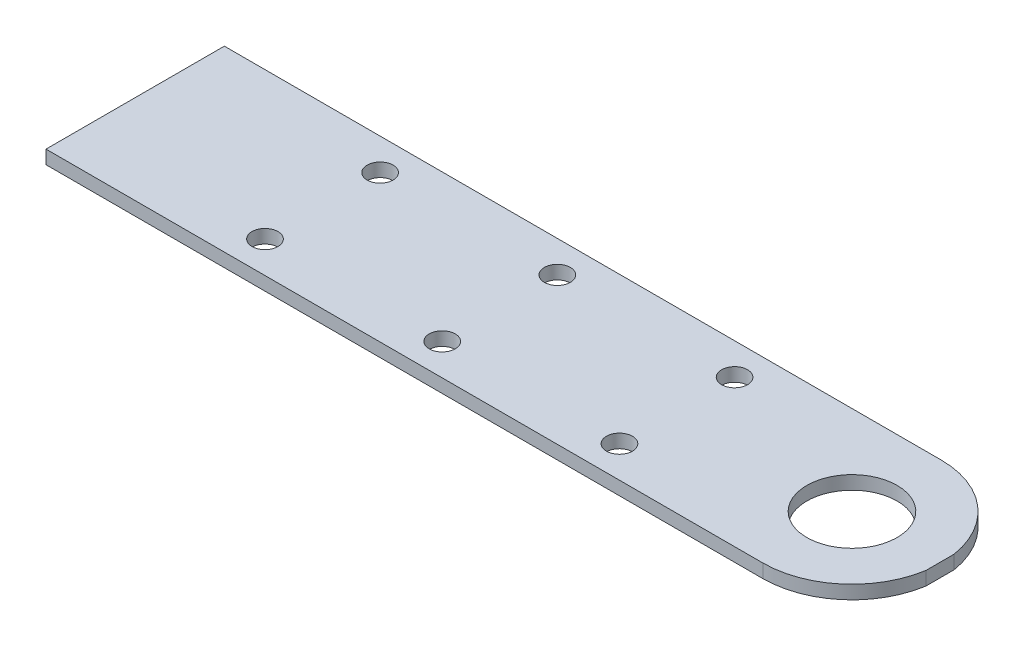
SolidWorks part; units mm, degrees
ref_plane "Front Plane" through (0, 0, 0) normal (0, 0, 1) x (1, 0, 0)
ref_plane "Top Plane" through (0, 0, 0) normal (0, 1, 0) x (1, 0, 0)
ref_plane "Right Plane" through (0, 0, 0) normal (1, 0, 0) x (0, 0, -1)
sketch "Sketch1" plane through (0, 0, 0) normal (0, 1, 0) x (1, 0, 0)
  line L0 (-69.469, 16.51) -> (-49.53, 16.51) construction
  line L1 (0, 0) -> (-90.551, 0)
  line L2 (0, 0) -> (0, 20.066)
  line L3 (0, 20.066) -> (-90.551, 20.066)
  line L4 (-90.551, 0) -> (-90.551, 20.066)
  line L5 (-29.591, 16.51) -> (-49.53, 16.51) construction
  line L6 (-29.591, 16.51) -> (-29.591, 20.066) construction
  line L7 (-29.591, 3.556) -> (-29.591, 0) construction
  line L8 (-9.906, 10.033) -> (-9.906, 20.066) construction
  line L9 (-9.906, 10.033) -> (-9.906, 0) construction
  line L10 (-4.826, 10.033) -> (0, 10.033) construction
  circle A0 centre (-69.469, 16.51) radius 1.4605
  circle A1 centre (-69.469, 3.556) radius 1.4605
  circle A2 centre (-49.53, 16.51) radius 1.4605
  circle A3 centre (-49.53, 3.556) radius 1.4605
  circle A4 centre (-29.591, 16.51) radius 1.4605
  circle A5 centre (-29.591, 3.556) radius 1.4605
  circle A6 centre (-9.906, 10.033) radius 5.08
  arc A7 (-9.906, 0) -> (-9.906, 20.066) centre (-9.906, 10.033) ccw
  dimension "D3" = 2.921
  dimension "D4" = 3.556
  dimension "D5" = 0
  dimension "D6" = 0
  dimension "D7" = 0
  dimension "D8" = 0
  dimension "D9" = 0
  dimension "D10" = 0
  dimension "D11" = 0
  dimension "D12" = 19.939
  dimension "D13" = 29.591
  dimension "D14" = 10.16
  dimension "D1" = 20.066
  dimension "D2" = 90.551
  dimension "D15" = 4.826
extrude "Boss-Extrude1" add sketch "Sketch1" along normal blind 1.524 contours L1 A7 L2 L3 L4 A6 A5 A4 A3 A2 A1 A0
